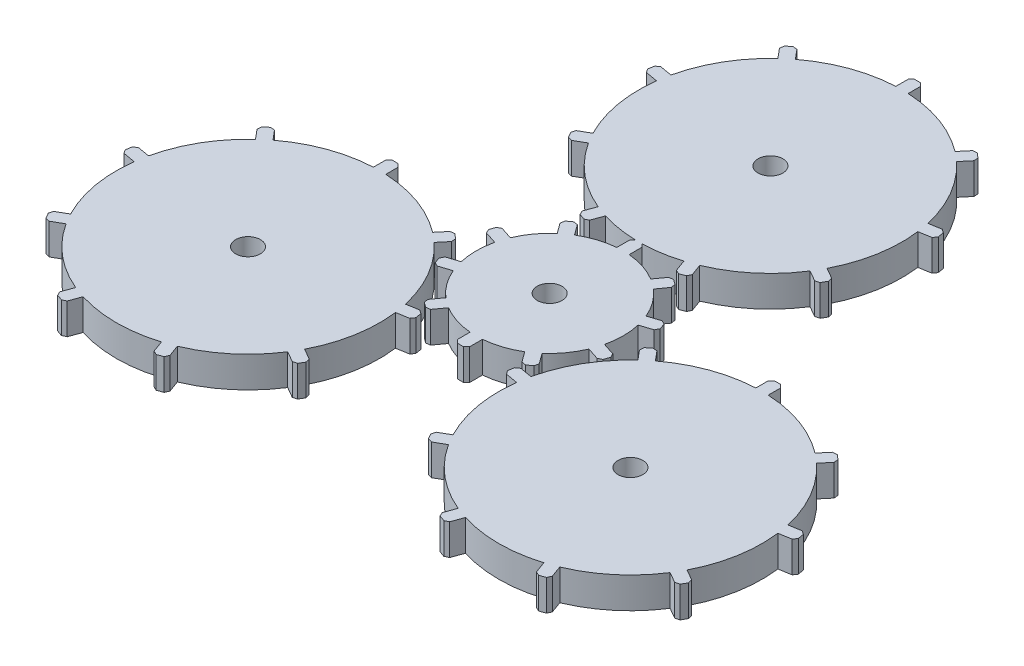
SolidWorks part; units mm, degrees
ref_plane "前基準面" through (0, 0, 0) normal (0, 0, 1) x (1, 0, 0)
ref_plane "上基準面" through (0, 0, 0) normal (0, 1, 0) x (1, 0, 0)
ref_plane "右基準面" through (0, 0, 0) normal (1, 0, 0) x (0, 0, -1)
sketch "草圖1" plane through (0, 0, 0) normal (0, 1, 0) x (1, 0, 0)
  line L0 (0, 0) -> (0, 22.2298) construction
  line L6 (-1, 118.7079) -> (-2, 117.7079)
  line L11 (2, 113.7029) -> (2, 117.7079)
  line L12 (1, 118.7079) -> (-1, 118.7079)
  line L17 (-2, 113.7029) -> (-2, 117.7079)
  line L18 (2, 117.7079) -> (1, 118.7079)
  line L23 (25.7561, 105.0564) -> (28.3305, 108.1244)
  line L24 (29.7393, 108.2476) -> (28.3305, 108.1244)
  line L29 (31.2714, 106.9621) -> (29.7393, 108.2476)
  line L30 (31.3946, 105.5532) -> (31.2714, 106.9621)
  line L35 (28.8203, 102.4852) -> (31.3946, 105.5532)
  line L36 (41.4607, 80.5915) -> (45.4048, 81.2869)
  line L41 (46.5632, 80.4758) -> (45.4048, 81.2869)
  line L42 (46.9105, 78.5062) -> (46.5632, 80.4758)
  line L47 (46.0994, 77.3477) -> (46.9105, 78.5062)
  line L48 (42.1553, 76.6523) -> (46.0994, 77.3477)
  line L53 (37.7653, 51.7556) -> (41.2337, 49.7531)
  line L54 (41.5997, 48.3871) -> (41.2337, 49.7531)
  line L59 (40.5997, 46.655) -> (41.5997, 48.3871)
  line L60 (39.2337, 46.289) -> (40.5997, 46.655)
  line L61 (35.7653, 48.2915) -> (39.2337, 46.289)
  line L62 (16.3991, 32.0413) -> (17.7689, 28.2779)
  line L63 (17.1712, 26.9962) -> (17.7689, 28.2779)
  line L64 (15.2919, 26.3122) -> (17.1712, 26.9962)
  line L65 (14.0101, 26.9098) -> (15.2919, 26.3122)
  line L66 (12.6404, 30.6733) -> (14.0101, 26.9098)
  line L67 (-12.6404, 30.6733) -> (-14.0101, 26.9098)
  line L78 (-15.2919, 26.3122) -> (-14.0101, 26.9098)
  line L79 (-17.1712, 26.9962) -> (-15.2919, 26.3122)
  line L80 (-17.7689, 28.2779) -> (-17.1712, 26.9962)
  line L81 (-16.3991, 32.0413) -> (-17.7689, 28.2779)
  line L82 (-35.7653, 48.2915) -> (-39.2337, 46.289)
  line L83 (-40.5997, 46.655) -> (-39.2337, 46.289)
  line L84 (-41.5997, 48.3871) -> (-40.5997, 46.655)
  line L85 (-41.2337, 49.7531) -> (-41.5997, 48.3871)
  line L86 (-37.7653, 51.7556) -> (-41.2337, 49.7531)
  line L87 (-42.1553, 76.6523) -> (-46.0994, 77.3477)
  line L88 (-46.9105, 78.5062) -> (-46.0994, 77.3477)
  line L89 (-46.5632, 80.4758) -> (-46.9105, 78.5062)
  line L90 (-45.4048, 81.2869) -> (-46.5632, 80.4758)
  line L91 (-41.4607, 80.5915) -> (-45.4048, 81.2869)
  line L92 (-28.8203, 102.4852) -> (-31.3946, 105.5532)
  line L93 (-31.2714, 106.9621) -> (-31.3946, 105.5532)
  line L94 (-29.7393, 108.2476) -> (-31.2714, 106.9621)
  line L95 (-28.3305, 108.1244) -> (-29.7393, 108.2476)
  line L96 (-25.7561, 105.0564) -> (-28.3305, 108.1244)
  line L97 (-2, 23.6656) -> (-2, 27.7971)
  line L98 (-1, 28.7971) -> (1, 28.7971)
  line L99 (2, 27.7971) -> (2, 23.6656)
  line L100 (-2, 27.7971) -> (-1, 28.7971)
  line L101 (1, 28.7971) -> (2, 27.7971)
  line L102 (14.7207, 23.6639) -> (16.1175, 23.8851)
  line L103 (16.1175, 23.8851) -> (17.7355, 22.7095)
  line L104 (17.7355, 22.7095) -> (17.9568, 21.3127)
  line L105 (17.9568, 21.3127) -> (15.5283, 17.9703)
  line L106 (12.2923, 20.3215) -> (14.7207, 23.6639)
  line L107 (25.8186, 10.4919) -> (27.0786, 9.8498)
  line L108 (27.0786, 9.8498) -> (27.6967, 7.9477)
  line L109 (27.6967, 7.9477) -> (27.0546, 6.6877)
  line L110 (27.0546, 6.6877) -> (23.1254, 5.411)
  line L111 (21.8893, 9.2152) -> (25.8186, 10.4919)
  line L112 (27.0546, -6.6877) -> (27.6967, -7.9477)
  line L113 (27.6967, -7.9477) -> (27.0786, -9.8498)
  line L114 (27.0786, -9.8498) -> (25.8186, -10.4919)
  line L115 (25.8186, -10.4919) -> (21.8893, -9.2152)
  line L116 (23.1254, -5.411) -> (27.0546, -6.6877)
  line L117 (17.9568, -21.3127) -> (17.7355, -22.7095)
  line L118 (17.7355, -22.7095) -> (16.1175, -23.8851)
  line L119 (16.1175, -23.8851) -> (14.7207, -23.6639)
  line L120 (14.7207, -23.6639) -> (12.2923, -20.3215)
  line L121 (15.5283, -17.9703) -> (17.9568, -21.3127)
  line L122 (2, -27.7971) -> (1, -28.7971)
  line L123 (1, -28.7971) -> (-1, -28.7971)
  line L124 (-1, -28.7971) -> (-2, -27.7971)
  line L125 (-2, -27.7971) -> (-2, -23.6656)
  line L126 (2, -23.6656) -> (2, -27.7971)
  line L127 (-14.7207, -23.6639) -> (-16.1175, -23.8851)
  line L128 (-16.1175, -23.8851) -> (-17.7355, -22.7095)
  line L129 (-17.7355, -22.7095) -> (-17.9568, -21.3127)
  line L130 (-17.9568, -21.3127) -> (-15.5283, -17.9703)
  line L131 (-12.2923, -20.3215) -> (-14.7207, -23.6639)
  line L132 (-25.8186, -10.4919) -> (-27.0786, -9.8498)
  line L133 (-27.0786, -9.8498) -> (-27.6967, -7.9477)
  line L134 (-27.6967, -7.9477) -> (-27.0546, -6.6877)
  line L135 (-27.0546, -6.6877) -> (-23.1254, -5.411)
  line L136 (-21.8893, -9.2152) -> (-25.8186, -10.4919)
  line L137 (-27.0546, 6.6877) -> (-27.6967, 7.9477)
  line L138 (-27.6967, 7.9477) -> (-27.0786, 9.8498)
  line L139 (-27.0786, 9.8498) -> (-25.8186, 10.4919)
  line L140 (-25.8186, 10.4919) -> (-21.8893, 9.2152)
  line L141 (-23.1254, 5.411) -> (-27.0546, 6.6877)
  line L142 (-17.9568, 21.3127) -> (-17.7355, 22.7095)
  line L143 (-17.7355, 22.7095) -> (-16.1175, 23.8851)
  line L144 (-16.1175, 23.8851) -> (-14.7207, 23.6639)
  line L145 (-14.7207, 23.6639) -> (-12.2923, 20.3215)
  line L146 (-15.5283, 17.9703) -> (-17.9568, 21.3127)
  line L147 (-23.939, -55.1194) -> (-20.4706, -57.1219)
  line L148 (-20.1046, -58.4879) -> (-20.4706, -57.1219)
  line L149 (-21.1046, -60.22) -> (-20.1046, -58.4879)
  line L150 (-22.4706, -60.586) -> (-21.1046, -60.22)
  line L151 (-25.939, -58.5835) -> (-22.4706, -60.586)
  line L152 (-45.3052, -74.8337) -> (-43.9354, -78.5971)
  line L153 (-44.5331, -79.8788) -> (-43.9354, -78.5971)
  line L154 (-46.4125, -80.5628) -> (-44.5331, -79.8788)
  line L155 (-47.6942, -79.9652) -> (-46.4125, -80.5628)
  line L156 (-49.0639, -76.2017) -> (-47.6942, -79.9652)
  line L157 (-74.3447, -76.2017) -> (-75.7145, -79.9652)
  line L158 (-76.9962, -80.5628) -> (-75.7145, -79.9652)
  line L159 (-78.8756, -79.8788) -> (-76.9962, -80.5628)
  line L160 (-79.4732, -78.5971) -> (-78.8756, -79.8788)
  line L161 (-78.1034, -74.8337) -> (-79.4732, -78.5971)
  line L162 (-97.4696, -58.5835) -> (-100.938, -60.586)
  line L163 (-102.304, -60.22) -> (-100.938, -60.586)
  line L164 (-103.304, -58.4879) -> (-102.304, -60.22)
  line L165 (-102.938, -57.1219) -> (-103.304, -58.4879)
  line L166 (-99.4696, -55.1194) -> (-102.938, -57.1219)
  line L167 (-103.8596, -30.2227) -> (-107.8037, -29.5273)
  line L168 (-108.6148, -28.3688) -> (-107.8037, -29.5273)
  line L169 (-108.2675, -26.3992) -> (-108.6148, -28.3688)
  line L170 (-107.1091, -25.5881) -> (-108.2675, -26.3992)
  line L171 (-103.165, -26.2835) -> (-107.1091, -25.5881)
  line L172 (-90.5246, -4.3898) -> (-93.0989, -1.3218)
  line L173 (-92.9757, 0.0871) -> (-93.0989, -1.3218)
  line L174 (-91.4436, 1.3726) -> (-92.9757, 0.0871)
  line L175 (-90.0348, 1.2494) -> (-91.4436, 1.3726)
  line L176 (-87.4604, -1.8186) -> (-90.0348, 1.2494)
  line L177 (-63.7043, 6.8279) -> (-63.7043, 10.8329)
  line L178 (-62.7043, 11.8329) -> (-63.7043, 10.8329)
  line L179 (-60.7043, 11.8329) -> (-62.7043, 11.8329)
  line L180 (-59.7043, 10.8329) -> (-60.7043, 11.8329)
  line L181 (-59.7043, 6.8279) -> (-59.7043, 10.8329)
  line L182 (-35.9482, -1.8186) -> (-33.3739, 1.2494)
  line L183 (-31.965, 1.3726) -> (-33.3739, 1.2494)
  line L184 (-30.4329, 0.0871) -> (-31.965, 1.3726)
  line L185 (-30.3097, -1.3218) -> (-30.4329, 0.0871)
  line L186 (-32.884, -4.3898) -> (-30.3097, -1.3218)
  line L187 (-20.2436, -26.2835) -> (-16.2995, -25.5881)
  line L188 (-15.1411, -26.3992) -> (-16.2995, -25.5881)
  line L189 (-14.7938, -28.3688) -> (-15.1411, -26.3992)
  line L190 (-15.6049, -29.5273) -> (-14.7938, -28.3688)
  line L191 (-19.5491, -30.2227) -> (-15.6049, -29.5273)
  line L192 (59.7043, 6.8279) -> (59.7043, 10.8329)
  line L193 (60.7043, 11.8329) -> (59.7043, 10.8329)
  line L194 (62.7043, 11.8329) -> (60.7043, 11.8329)
  line L195 (63.7043, 10.8329) -> (62.7043, 11.8329)
  line L196 (63.7043, 6.8279) -> (63.7043, 10.8329)
  line L197 (87.4604, -1.8186) -> (90.0348, 1.2494)
  line L198 (91.4436, 1.3726) -> (90.0348, 1.2494)
  line L199 (92.9757, 0.0871) -> (91.4436, 1.3726)
  line L200 (93.0989, -1.3218) -> (92.9757, 0.0871)
  line L201 (90.5246, -4.3898) -> (93.0989, -1.3218)
  line L202 (103.165, -26.2835) -> (107.1091, -25.5881)
  line L203 (108.2675, -26.3992) -> (107.1091, -25.5881)
  line L204 (108.6148, -28.3688) -> (108.2675, -26.3992)
  line L205 (107.8037, -29.5273) -> (108.6148, -28.3688)
  line L206 (103.8596, -30.2227) -> (107.8037, -29.5273)
  line L207 (99.4696, -55.1194) -> (102.938, -57.1219)
  line L208 (103.304, -58.4879) -> (102.938, -57.1219)
  line L209 (102.304, -60.22) -> (103.304, -58.4879)
  line L210 (100.938, -60.586) -> (102.304, -60.22)
  line L211 (97.4696, -58.5835) -> (100.938, -60.586)
  line L212 (78.1034, -74.8337) -> (79.4732, -78.5971)
  line L213 (78.8756, -79.8788) -> (79.4732, -78.5971)
  line L214 (76.9962, -80.5628) -> (78.8756, -79.8788)
  line L215 (75.7145, -79.9652) -> (76.9962, -80.5628)
  line L216 (74.3447, -76.2017) -> (75.7145, -79.9652)
  line L217 (49.0639, -76.2017) -> (47.6942, -79.9652)
  line L218 (46.4125, -80.5628) -> (47.6942, -79.9652)
  line L219 (44.5331, -79.8788) -> (46.4125, -80.5628)
  line L220 (43.9354, -78.5971) -> (44.5331, -79.8788)
  line L221 (45.3052, -74.8337) -> (43.9354, -78.5971)
  line L222 (25.939, -58.5835) -> (22.4706, -60.586)
  line L223 (21.1046, -60.22) -> (22.4706, -60.586)
  line L224 (20.1046, -58.4879) -> (21.1046, -60.22)
  line L225 (20.4706, -57.1219) -> (20.1046, -58.4879)
  line L226 (23.939, -55.1194) -> (20.4706, -57.1219)
  line L227 (19.5491, -30.2227) -> (15.6049, -29.5273)
  line L228 (14.7938, -28.3688) -> (15.6049, -29.5273)
  line L229 (15.1411, -26.3992) -> (14.7938, -28.3688)
  line L230 (16.2995, -25.5881) -> (15.1411, -26.3992)
  line L231 (20.2436, -26.2835) -> (16.2995, -25.5881)
  line L232 (32.884, -4.3898) -> (30.3097, -1.3218)
  line L233 (30.4329, 0.0871) -> (30.3097, -1.3218)
  line L234 (31.965, 1.3726) -> (30.4329, 0.0871)
  line L235 (33.3739, 1.2494) -> (31.965, 1.3726)
  line L236 (35.9482, -1.8186) -> (33.3739, 1.2494)
  circle A1 centre (0, 0) radius 26.25 construction
  circle A11 centre (0, 0) radius 28.75 construction
  circle A12 centre (0, 0) radius 4
  arc A13 (-23.1254, 5.411) -> (-23.1254, -5.411) centre (0, 0) ccw
  circle A34 centre (0, 0) radius 23.75 construction
  arc A35 (-15.5283, 17.9703) -> (-21.8893, 9.2152) centre (0, 0) ccw
  arc A36 (-2, 23.6656) -> (-12.2923, 20.3215) centre (0, 0) ccw
  arc A37 (12.2923, 20.3215) -> (2, 23.6656) centre (0, 0) ccw
  arc A38 (21.8893, 9.2152) -> (15.5283, 17.9703) centre (0, 0) ccw
  arc A39 (23.1254, -5.411) -> (23.1254, 5.411) centre (0, 0) ccw
  arc A40 (15.5283, -17.9703) -> (21.8893, -9.2152) centre (0, 0) ccw
  arc A41 (2, -23.6656) -> (12.2923, -20.3215) centre (0, 0) ccw
  arc A42 (-12.2923, -20.3215) -> (-2, -23.6656) centre (0, 0) ccw
  arc A43 (-21.8893, -9.2152) -> (-15.5283, -17.9703) centre (0, 0) ccw
  circle A44 centre (0, 71.25) radius 47.5 construction
  circle A45 centre (0, 71.25) radius 45 construction
  circle A46 centre (0, 71.25) radius 4
  arc A47 (-42.1553, 76.6523) -> (-37.7653, 51.7556) centre (0, 71.25) ccw
  circle A48 centre (0, 71.25) radius 42.5 construction
  arc A49 (-28.8203, 102.4852) -> (-41.4607, 80.5915) centre (0, 71.25) ccw
  arc A50 (-2, 113.7029) -> (-25.7561, 105.0564) centre (0, 71.25) ccw
  arc A51 (25.7561, 105.0564) -> (2, 113.7029) centre (0, 71.25) ccw
  arc A52 (41.4607, 80.5915) -> (28.8203, 102.4852) centre (0, 71.25) ccw
  arc A53 (37.7653, 51.7556) -> (42.1553, 76.6523) centre (0, 71.25) ccw
  arc A54 (16.3991, 32.0413) -> (35.7653, 48.2915) centre (0, 71.25) ccw
  arc A55 (-12.6404, 30.6733) -> (12.6404, 30.6733) centre (0, 71.25) ccw
  arc A56 (-35.7653, 48.2915) -> (-16.3991, 32.0413) centre (0, 71.25) ccw
  arc A57 (-45.3052, -74.8337) -> (-25.939, -58.5835) centre (-61.7043, -35.625) ccw
  arc A58 (-74.3447, -76.2017) -> (-49.0639, -76.2017) centre (-61.7043, -35.625) ccw
  arc A59 (-97.4696, -58.5835) -> (-78.1034, -74.8337) centre (-61.7043, -35.625) ccw
  arc A60 (-103.8596, -30.2227) -> (-99.4696, -55.1194) centre (-61.7043, -35.625) ccw
  arc A61 (-90.5246, -4.3898) -> (-103.165, -26.2835) centre (-61.7043, -35.625) ccw
  arc A62 (-63.7043, 6.8279) -> (-87.4604, -1.8186) centre (-61.7043, -35.625) ccw
  arc A63 (-35.9482, -1.8186) -> (-59.7043, 6.8279) centre (-61.7043, -35.625) ccw
  arc A64 (-20.2436, -26.2835) -> (-32.884, -4.3898) centre (-61.7043, -35.625) ccw
  arc A65 (-23.939, -55.1194) -> (-19.5491, -30.2227) centre (-61.7043, -35.625) ccw
  circle A66 centre (-61.7043, -35.625) radius 4
  arc A67 (87.4604, -1.8186) -> (63.7043, 6.8279) centre (61.7043, -35.625) ccw
  arc A68 (103.165, -26.2835) -> (90.5246, -4.3898) centre (61.7043, -35.625) ccw
  arc A69 (99.4696, -55.1194) -> (103.8596, -30.2227) centre (61.7043, -35.625) ccw
  arc A70 (78.1034, -74.8337) -> (97.4696, -58.5835) centre (61.7043, -35.625) ccw
  arc A71 (49.0639, -76.2017) -> (74.3447, -76.2017) centre (61.7043, -35.625) ccw
  arc A72 (25.939, -58.5835) -> (45.3052, -74.8337) centre (61.7043, -35.625) ccw
  arc A73 (19.5491, -30.2227) -> (23.939, -55.1194) centre (61.7043, -35.625) ccw
  arc A74 (32.884, -4.3898) -> (20.2436, -26.2835) centre (61.7043, -35.625) ccw
  arc A75 (59.7043, 6.8279) -> (35.9482, -1.8186) centre (61.7043, -35.625) ccw
  circle A76 centre (61.7043, -35.625) radius 4
  point P1 (-9.6985, 13.3488)
  point P5 (15.6924, -5.0988)
  point P7 (-15.6924, 5.0988)
  point P8 (15.6924, 5.0988)
  point P11 (-15.6924, -5.0988)
  point P12 (9.6985, 13.3488)
  point P14 (-9.6985, -13.3488)
  point P15 (0, -16.5)
  point P16 (-2, 28.7971)
  point P18 (2, 28.7971)
  point P24 (35.8141, -38.7522)
  point P26 (0, 0)
  point P67 (0, 0)
  point P75 (-2, 118.7079)
  point P76 (2, 118.7079)
  point P97 (0, 0)
  point P153 (0, 71.25)
  point P194 (0, 0)
  point P281 (0, 0)
  dimension "D1" = 52.5
  dimension "D2" = 57.5
  dimension "D3" = 8
  dimension "D5" = 4
  dimension "D6" = 95
  dimension "D7" = 90
  dimension "D9" = 8
  dimension "D11" = 4
  dimension "D4" = 5
  dimension "D8" = 71.25
  dimension "D12" = 9
  dimension "D15" = 10
  dimension "D10" = 5
  dimension "D16" = 3
extrude "填料-伸長1" add sketch "草圖1" along normal blind 10
